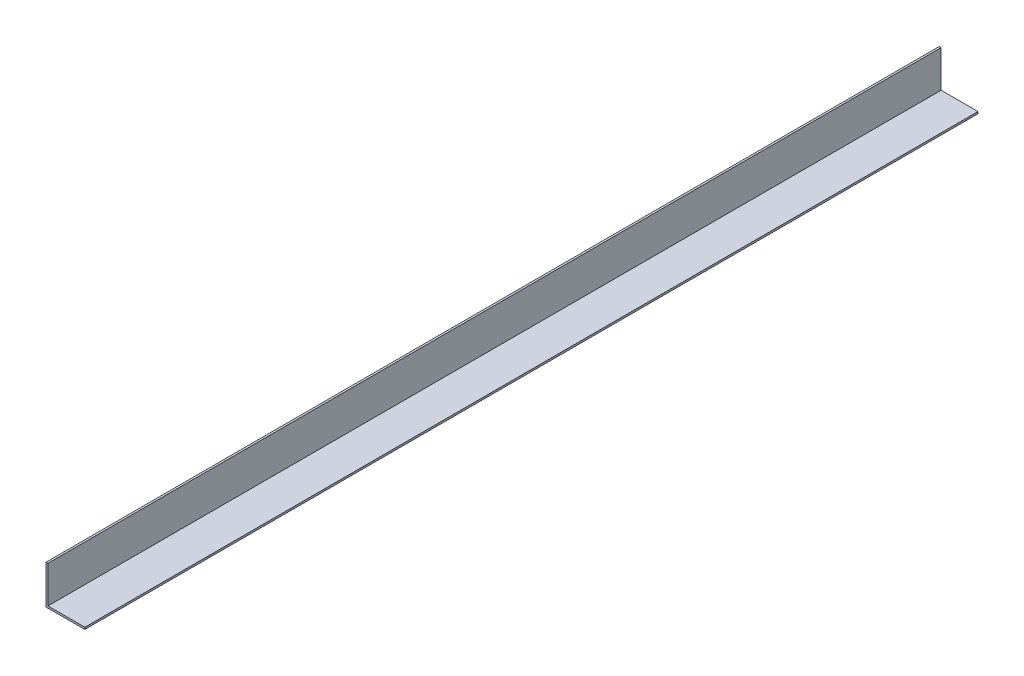
SolidWorks part; units mm, degrees
material "1060 合金"
ref_plane "前视基准面" through (0, 0, 0) normal (0, 0, 1) x (1, 0, 0)
ref_plane "上视基准面" through (0, 0, 0) normal (0, 1, 0) x (1, 0, 0)
ref_plane "右视基准面" through (0, 0, 0) normal (1, 0, 0) x (0, 0, -1)
sketch "草图1" plane through (0, 0, 0) normal (0, 0, 1) x (1, 0, 0)
  line L0 (0, 0) -> (0, 20)
  line L1 (0, 20) -> (1, 20)
  line L2 (1, 20) -> (1, 1)
  line L3 (1, 1) -> (20, 1)
  line L4 (20, 1) -> (20, 0)
  line L5 (20, 0) -> (0, 0)
  dimension "D1" = 1
  dimension "D2" = 1
  dimension "D3" = 20
  dimension "D4" = 20
extrude "凸台-拉伸1" add sketch "草图1" along normal blind 460
